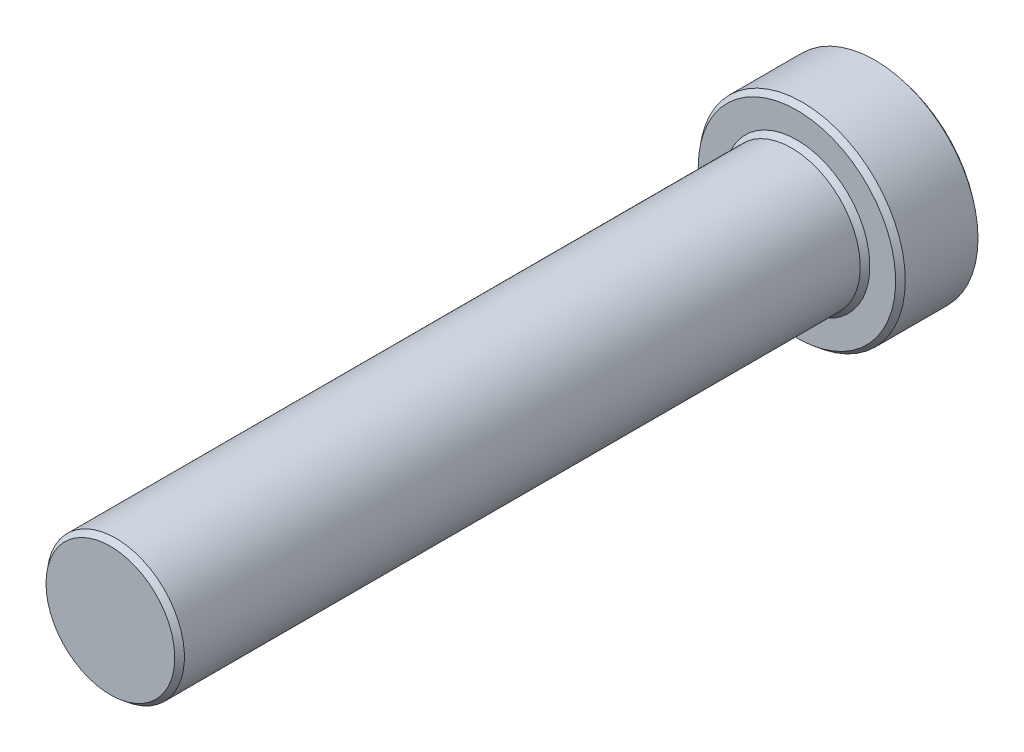
SolidWorks part; units mm, degrees
ref_plane "Front Plane" through (0, 0, 0) normal (0, 0, 1) x (1, 0, 0)
ref_plane "Top Plane" through (0, 0, 0) normal (0, 1, 0) x (1, 0, 0)
ref_plane "Right Plane" through (0, 0, 0) normal (1, 0, 0) x (0, 0, -1)
sketch "Sketch1" plane through (0, 0, 0) normal (0, 1, 0) x (1, 0, 0)
  line L0 (0, 35.8447) -> (0, -21.0777) construction
  line L1 (-10, 21.2974) -> (-10, -77.1408)
  line L2 (-10, -77.1408) -> (-9.3753, -77.9217)
  line L3 (-9.3753, -77.9217) -> (0, -77.9217)
  line L4 (-10, 21.2974) -> (-10.6247, 22.0783)
  line L5 (-10.6247, 22.0783) -> (-14.3753, 22.0783)
  line L6 (-14.3753, 22.0783) -> (-15, 22.8592)
  line L7 (-15, 22.8592) -> (-15, 33.4536)
  line L8 (-15, 33.4536) -> (-14.2191, 34.0783)
  line L9 (-14.2191, 34.0783) -> (0, 34.0783)
  line L10 (0, -77.9217) -> (0, 34.0783)
  dimension "D1" = 20
  dimension "D2" = 30
  dimension "D3" = 12
  dimension "D4" = 1
  dimension "D5" = 1
  dimension "D6" = 1
  dimension "D7" = 100
revolve "Revolve1" add sketch "Sketch1" angle 360 about L0
